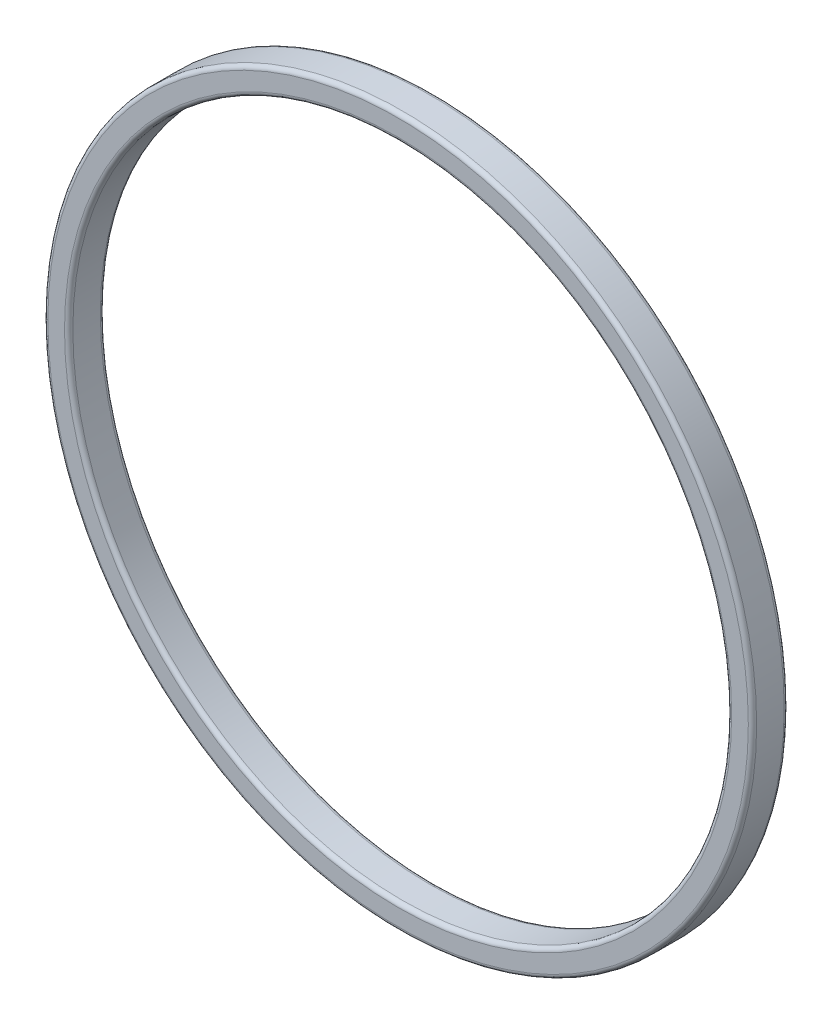
SolidWorks part; units mm, degrees
ref_plane "Front Plane" through (0, 0, 0) normal (0, 0, 1) x (1, 0, 0)
ref_plane "Top Plane" through (0, 0, 0) normal (0, 1, 0) x (1, 0, 0)
ref_plane "Right Plane" through (0, 0, 0) normal (1, 0, 0) x (0, 0, -1)
sketch "Sketch1" plane through (0, 0, 0) normal (0, 0, 1) x (1, 0, 0)
  circle A0 centre (0, 0) radius 42.5
  circle A1 centre (0, 0) radius 39.5
  dimension "D1" = 85
  dimension "D2" = 79
extrude "Boss-Extrude1" add sketch "Sketch1" along normal blind 4.3
fillet "Fillet1" radius 0.5 4 edges at (39.5, 0, 0) (42.5, 0, 0) (39.5, 0, 4.3) (42.5, 0, 4.3)
